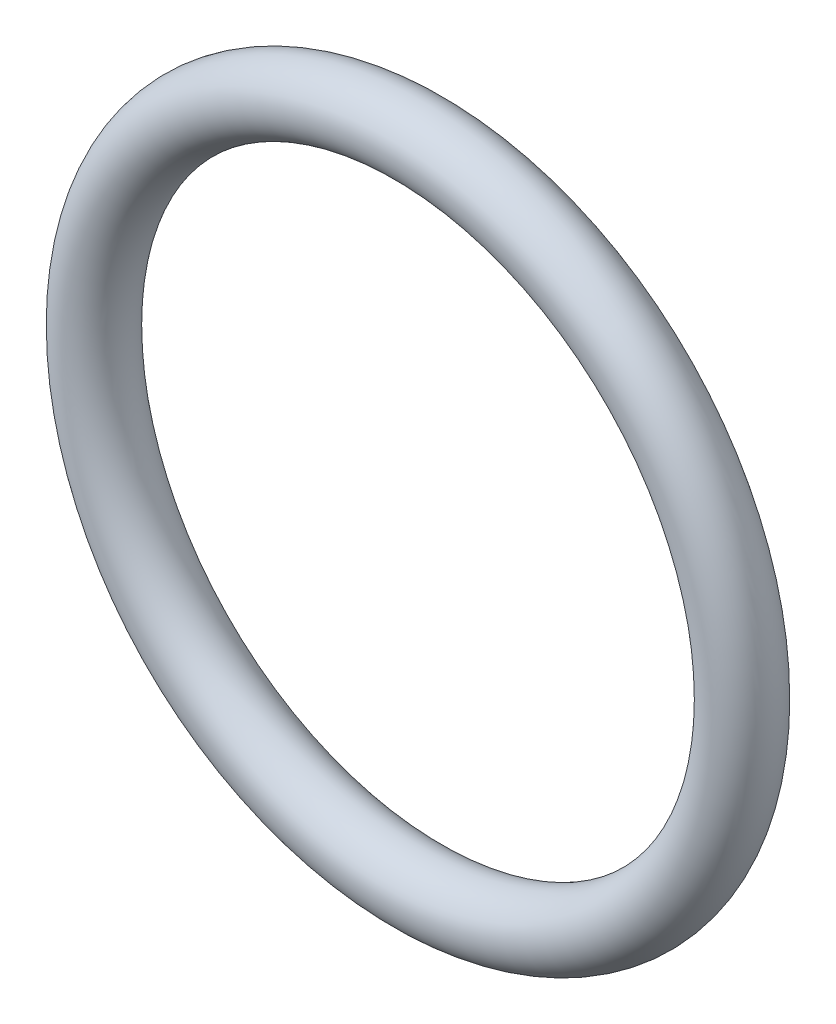
SolidWorks part; units mm, degrees
ref_plane "Front Plane" through (0, 0, 0) normal (0, 0, 1) x (1, 0, 0)
ref_plane "Top Plane" through (0, 0, 0) normal (0, 1, 0) x (1, 0, 0)
ref_plane "Right Plane" through (0, 0, 0) normal (1, 0, 0) x (0, 0, -1)
sketch "Sketch1" plane through (0, 0, 0) normal (0, 1, 0) x (1, 0, 0)
  line L0 (0, 0) -> (6, 0) construction
  line L1 (0, 0) -> (0, 0.9371) construction
  circle A0 centre (6, 0) radius 0.625
  dimension "D2" = 1.25
  dimension "D1" = 6
revolve "Revolve1" add sketch "Sketch1" angle 360 about L1
